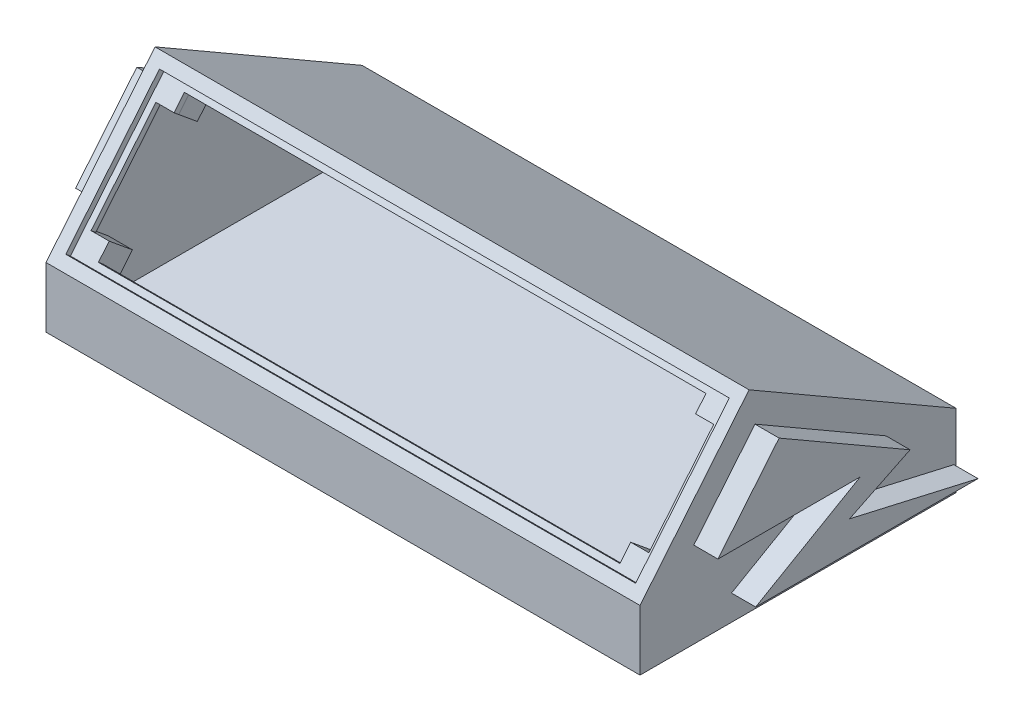
SolidWorks part; units mm, degrees
ref_plane "Front Plane" through (0, 0, 0) normal (0, 0, 1) x (1, 0, 0)
ref_plane "Top Plane" through (0, 0, 0) normal (0, 1, 0) x (1, 0, 0)
ref_plane "Right Plane" through (0, 0, 0) normal (1, 0, 0) x (0, 0, -1)
sketch "Sketch1" plane through (0, 0, 0) normal (1, 0, 0) x (0, 0, -1)
  line L0 (42.0739, 65.0414) -> (127.8104, 15.5414)
  line L5 (127.8104, 15.5414) -> (127.8104, -14.7157)
  line L6 (-4.3853, -14.7157) -> (164.6147, -14.7157) construction
  line L7 (127.8104, -14.7157) -> (-3.084, -14.7157)
  line L13 (-3.084, 10.2843) -> (-3.084, -14.7157)
  line L14 (-3.084, 10.2843) -> (42.0739, 65.0414)
  point P0 (0, 0)
extrude "Boss-Extrude2" add sketch "Sketch1" along normal mid plane 246
sketch "Sketch3" plane through (0, 0, 0) normal (1, 0, 0) x (0, 0, -1)
  line L10 (43.2388, 58.5953) -> (1.916, 8.4885)
  line L11 (1.916, 8.4885) -> (1.916, -9.7157)
  line L12 (1.916, -9.7157) -> (122.8104, -9.7157)
  line L13 (122.8104, -9.7157) -> (122.8104, 12.6547)
  line L14 (122.8104, 12.6547) -> (43.2388, 58.5953)
  line L15 (43.2388, 58.5953) -> (1.916, 8.4885)
  line L16 (1.916, 8.4885) -> (1.916, -9.7157)
  line L17 (1.916, -9.7157) -> (122.8104, -9.7157)
  line L18 (122.8104, -9.7157) -> (122.8104, 12.6547)
  line L19 (122.8104, 12.6547) -> (43.2388, 58.5953)
  dimension "D1" = 5
extrude "Cut-Extrude2" cut sketch "Sketch3" against normal mid plane 236 contours L15 L16 L17 L18 L19
sketch "Sketch4" plane through (0, 5.6769, 6.8837) normal (0, 0.6362, 0.7715) x (1, 0, 0)
  line L8 (-118, 71.9479) -> (-118, 10.9721)
  line L9 (-118, 10.9721) -> (118, 10.9721)
  line L10 (118, 10.9721) -> (118, 71.9479)
  line L11 (118, 71.9479) -> (-118, 71.9479)
  line L12 (-118, 71.9479) -> (-118, 10.9721)
  line L13 (-118, 10.9721) -> (118, 10.9721)
  line L14 (118, 10.9721) -> (118, 71.9479)
  line L15 (118, 71.9479) -> (-118, 71.9479)
  dimension "D1" = 5
extrude "Cut-Extrude3" cut sketch "Sketch4" against normal blind 2.5
sketch "Sketch5" plane through (0, 4.0863, 4.9549) normal (0, 0.6362, 0.7715) x (1, 0, 0)
  line L0 (107.5777, 69.4479) -> (107.9977, 69.4479)
  line L8 (115.5, 69.4479) -> (-115.5, 69.4479)
  line L9 (-115.5, 69.4479) -> (-115.5, 13.4721)
  line L10 (-115.5, 13.4721) -> (115.5, 13.4721)
  line L11 (115.5, 13.4721) -> (115.5, 69.4479)
  line L12 (107.5777, 69.4479) -> (-107.9977, 69.4479)
  line L13 (-115.5, 62.7146) -> (-115.5, 20.4721)
  line L14 (-107.9977, 13.4721) -> (107.9977, 13.4721)
  line L15 (115.5, 20.4721) -> (115.5, 62.4479)
  line L19 (107.9977, 69.4479) -> (107.9977, 62.7146)
  line L26 (115.5, 62.6146) -> (115.5, 62.4479)
  line L27 (0, -43.8664) -> (0, 43.8664) construction
  line L31 (115.5, 62.6146) -> (115.5, 62.6646)
  line L34 (107.9977, 62.7146) -> (115.5, 62.7146)
  line L35 (115.5, 62.6646) -> (115.5, 62.7146)
  line L36 (-107.9977, 69.4479) -> (-107.9977, 62.7146)
  line L37 (-107.9977, 62.7146) -> (-115.5, 62.7146)
  line L38 (107.9977, 20.4721) -> (107.9977, 13.4721)
  line L39 (115.5, 20.4721) -> (107.9977, 20.4721)
  line L40 (-107.9977, 20.4721) -> (-107.9977, 13.4721)
  line L41 (-115.5, 20.4721) -> (-107.9977, 20.4721)
  dimension "D2" = 0.05
  dimension "D3" = 0.42
  dimension "D4" = 7
  dimension "D5" = 7.5023
  dimension "D1" = 2.5
extrude "Cut-Extrude4" cut sketch "Sketch5" against normal blind 2.5
sketch "Sketch6" plane through (-123, 0, 0) normal (-1, 0, 0) x (0, 0, 1)
  line L0 (-99.8291, 20.1495) -> (-44.4038, 52.1493)
  line L5 (-44.4038, 52.1493) -> (-18.1249, 20.2843) construction
  line L6 (-99.8291, 20.1495) -> (-44.4038, 52.1493) construction
  line L7 (-44.4038, 52.1493) -> (-18.1249, 20.2843)
  line L8 (-18.1249, 20.2843) -> (-76.2365, 20.2843)
  line L9 (-76.2365, 20.2843) -> (-32.9353, -4.7157)
  line L10 (-32.9353, -4.7157) -> (-131.3101, -4.7157)
  line L11 (-131.3101, -4.7157) -> (-75.1843, 8.1294) construction
  line L12 (-32.9353, -4.7157) -> (-131.3101, -4.7157) construction
  line L13 (-131.3101, -4.7157) -> (-75.1843, 8.1294)
  line L14 (-75.1843, 8.1294) -> (-99.8291, 20.1495) construction
  line L15 (-75.1843, 8.1294) -> (-99.8291, 20.1495)
  line L16 (-73.6922, 7.958) -> (-98.7647, 20.1866)
  line L17 (-98.7647, 20.1866) -> (-44.5202, 51.5047)
  line L18 (-44.5202, 51.5047) -> (-19.1853, 20.7843)
  line L19 (-19.1853, 20.7843) -> (-78.1025, 20.7843)
  line L20 (-78.1025, 20.7843) -> (-34.8013, -4.2157)
  line L21 (-34.8013, -4.2157) -> (-126.8842, -4.2157)
  line L22 (-126.8842, -4.2157) -> (-73.6922, 7.958)
  point P0 (-63.3626, 19.2467)
  dimension "D1" = 0.5
extrude "Boss-Extrude4" add sketch "Sketch6" along normal blind 10 contours L16 L17 L18 L19 L20 L21 L22
mirror "Mirror1" about plane through (0, 0, 0) normal (1, 0, 0) of "Boss-Extrude4"
sketch "Sketch15" plane through (0, 2.4957, 3.0262) normal (0, -0.6362, -0.7715) x (-1, 0, 0)
  line L0 (-117.5, 72.2161) -> (-117.5, 63.2161)
  line L1 (-118, 72.7161) -> (-108, 72.7161)
  line L2 (-118, 72.7161) -> (-118, 62.7161)
  line L3 (-118, 62.7161) -> (-108, 62.7161)
  line L4 (-108, 72.7161) -> (-108, 62.7161)
  line L5 (-117.5, 63.2161) -> (-108.5, 63.2161)
  line L6 (-108.5, 72.2161) -> (-108.5, 63.2161)
  line L7 (-117.5, 72.2161) -> (-108.5, 72.2161)
  line L8 (0, 43.8664) -> (0, -43.8664) construction
  line L9 (118, 62.7161) -> (108, 62.7161)
  line L10 (108, 72.7161) -> (108, 62.7161)
  line L11 (118, 72.7161) -> (108, 72.7161)
  line L12 (118, 72.7161) -> (118, 62.7161)
  line L13 (117.5, 72.2161) -> (108.5, 72.2161)
  line L14 (108.5, 72.2161) -> (108.5, 63.2161)
  line L15 (117.5, 63.2161) -> (108.5, 63.2161)
  line L16 (117.5, 72.2161) -> (117.5, 63.2161)
  line L17 (-108.4977, 19.9721) -> (-108.4977, 10.9721)
  line L18 (-107.9977, 20.4721) -> (-118, 20.4721)
  line L19 (-107.9977, 20.4721) -> (-107.9977, 10.4721)
  line L20 (-107.9977, 10.4721) -> (-118, 10.4721)
  line L21 (-118, 20.4721) -> (-118, 10.4721)
  line L22 (-108.4977, 10.9721) -> (-117.5, 10.9721)
  line L23 (-117.5, 19.9721) -> (-117.5, 10.9721)
  line L24 (-108.4977, 19.9721) -> (-117.5, 19.9721)
  line L25 (107.9977, 20.4721) -> (107.9977, 10.4721)
  line L26 (107.9977, 10.4721) -> (118, 10.4721)
  line L27 (118, 20.4721) -> (118, 10.4721)
  line L28 (107.9977, 20.4721) -> (118, 20.4721)
  line L29 (108.4977, 19.9721) -> (117.5, 19.9721)
  line L30 (117.5, 19.9721) -> (117.5, 10.9721)
  line L31 (108.4977, 10.9721) -> (117.5, 10.9721)
  line L32 (108.4977, 19.9721) -> (108.4977, 10.9721)
  dimension "D1" = 10
  dimension "D2" = 10
  dimension "D4" = 10.0023
  dimension "D5" = 10
  dimension "D3" = 0.5
  dimension "D6" = 0.5
extrude "Boss-Extrude14" add sketch "Sketch15" along normal blind 10
